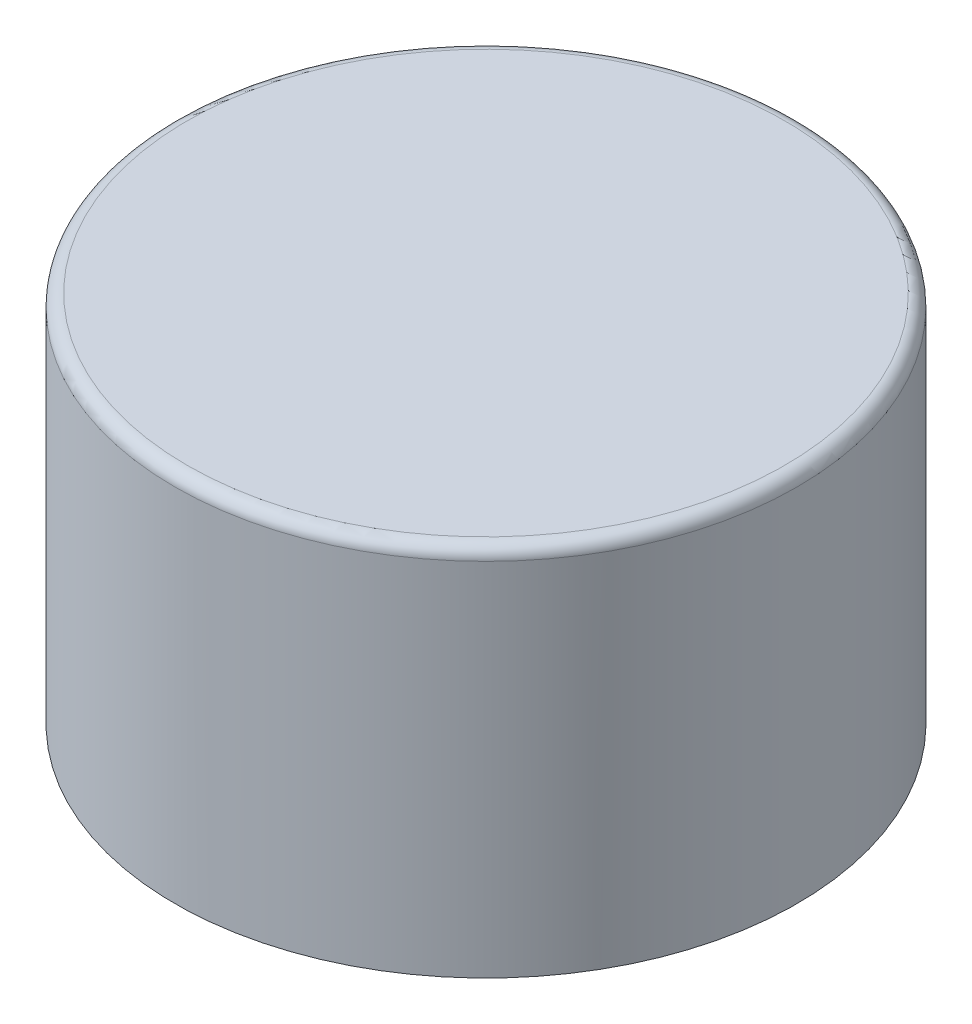
SolidWorks part; units mm, degrees
material "PVC Rigid"
ref_plane "Front Plane" through (0, 0, 0) normal (0, 0, 1) x (1, 0, 0)
ref_plane "Top Plane" through (0, 0, 0) normal (0, 1, 0) x (1, 0, 0)
ref_plane "Right Plane" through (0, 0, 0) normal (1, 0, 0) x (0, 0, -1)
sketch "Sketch1" plane through (0, 0, 0) normal (0, 1, 0) x (1, 0, 0)
  circle A0 centre (0, 0) radius 63.5
  dimension "D1" = 127
extrude "Boss-Extrude1" add sketch "Sketch1" along normal blind 76.2
shell "Shell1" thickness 6.35
fillet "Fillet1" radius 2.54 1 edges at (0, 76.2, 63.5)
